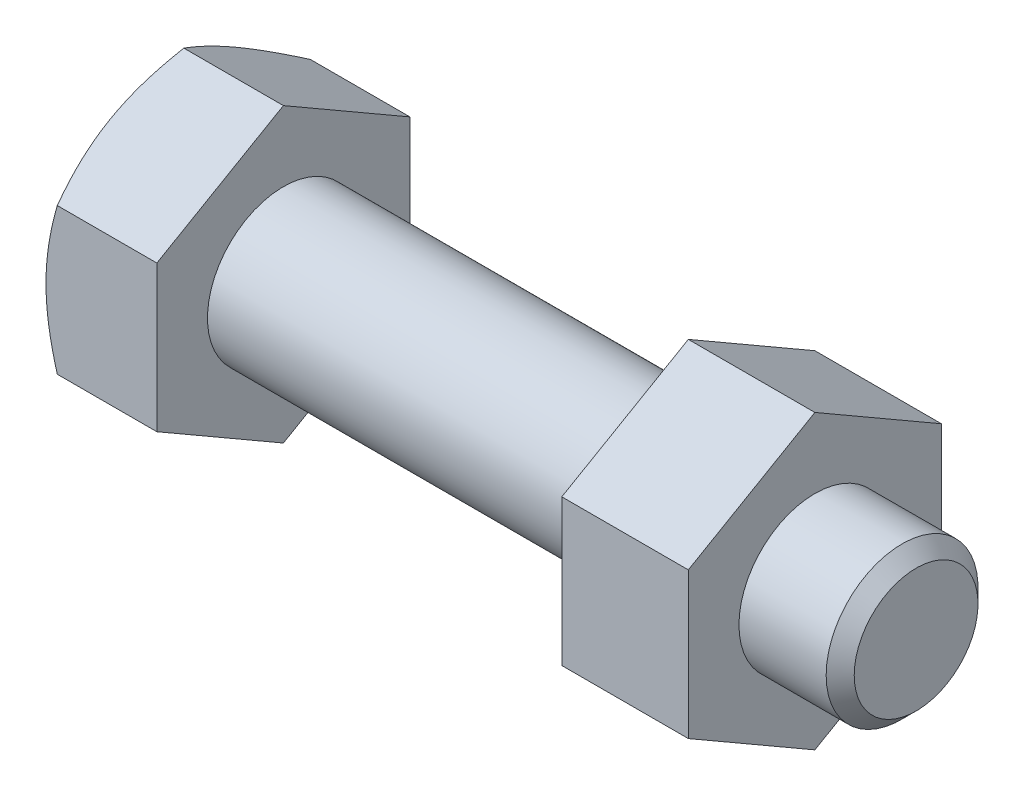
SolidWorks part; units mm, degrees
extrude "BaseHead" add sketch "Sketch1" along normal blind 4.38
sketch "Sketch1" plane through (0, 0, 0) normal (1, 0, 0) x (0, 0, -1)
  line L0 (5, 2.8868) -> (5, -2.8868)
  line L1 (-5, 2.8868) -> (-5, -2.8868)
  line L2 (5, -2.8868) -> (0, -5.7735)
  line L3 (0, -5.7735) -> (-5, -2.8868)
  line L4 (5, 2.8868) -> (0, 5.7735)
  line L5 (0, 5.7735) -> (-5, 2.8868)
  dimension "Width_flats" = 10
  dimension "D2" = 120
  dimension "D3" = 5
  dimension "D4" = 5
  dimension "D5" = 5
material "AISI 304"
ref_plane "Plane1" through (0, 0, 0) normal (0, 0, 1) x (1, 0, 0)
ref_plane "Plane2" through (0, 0, 0) normal (0, 1, 0) x (1, 0, 0)
ref_plane "Plane3" through (0, 0, 0) normal (1, 0, 0) x (0, 0, -1)
sketch "BodySke" plane through (0, 0, 0) normal (0, 0, 1) x (1, 0, 0)
  line L0 (0, 2.8868) -> (0, -2.8868) construction
  line L1 (0, 0) -> (29.38, 0)
  line L2 (0, 0) -> (0, 3)
  line L3 (0, 3) -> (28.8255, 3)
  line L4 (29.38, 0) -> (29.38, 2.4455)
  line L5 (4.38, 5.7735) -> (4.38, 2.8868) construction
  line L6 (29.38, 2.4455) -> (28.8255, 3)
  line L7 (0, 0) -> (96.52, 0) construction
  line L8 (29.38, -2.4455) -> (28.8255, -3) construction
  line L9 (0, -3) -> (28.8255, -3) construction
  line L10 (5.38, 15.24) -> (5.38, -1.27) construction
  line L11 (11.38, 15.24) -> (11.38, -1.27) construction
  line L12 (4.38, 2.8868) -> (4.38, -2.8868) construction
  dimension "Diameter" = 6
  dimension "Advance" = 1
revolve "BaseBody" add sketch "BodySke"
cosmetic thread "ThreadCosmetic" [suppressed]
fillet "HeadFillet" [suppressed] radius 0.25
sketch "Sketch3" plane through (0, 0, 0) normal (0, 0, 1) x (1, 0, 0)
  line L0 (0, 5) -> (3.3333, 10.7735)
  line L1 (0, 5.7735) -> (0, 2.8868) construction
  line L2 (3.3333, 10.7735) -> (3.3333, 15.7735)
  line L3 (3.3333, 15.7735) -> (-10, 15.7735)
  line L4 (-10, 15.7735) -> (-10, 5)
  line L5 (-10, 5) -> (0, 5)
  line L6 (0, 0) -> (99.06, 0) construction
  line L7 (4.38, 5.7735) -> (0, 5.7735) construction
  dimension "D4" = 5
  dimension "D1" = 5
  dimension "D2" = 5
  dimension "D3" = 10
  dimension "Head_ch_ang" = 30
revolve "HeadChamfer" cut sketch "Sketch3" angle 360 about L6
sketch "ThdSchSke" plane through (0, 0, 0) normal (0, 0, 1) x (1, 0, 0)
  line L0 (11.38, -2.4455) -> (10.9917, -3)
  line L1 (11.38, -2.4455) -> (11.7683, -3)
  line L2 (11.7683, -3) -> (11.7683, -3.75)
  line L3 (-3.175, 0) -> (5.1513, 0) construction
  line L5 (11.7683, -3.75) -> (10.9917, -3.75)
  line L6 (10.9917, -3.75) -> (10.9917, -3)
  dimension "Thread_minor" = 4.891
  dimension "Diameter" = 6
  dimension "Start" = 11.38
revolve "ThreadSchematic" [suppressed] cut sketch "ThdSchSke" angle 360 about L3
pattern_linear "ThdSchPat" [suppressed]
ref_plane "Plane4" through (25.38, 0, 0) normal (1, 0, 0) x (0, 0, -1)
sketch "Sketch4" plane through (25.38, 0, 0) normal (1, 0, 0) x (0, 0, -1)
  line L1 (0, 5.7735) -> (-5, 2.8868)
  line L2 (-5, 2.8868) -> (-5, -2.8868)
  line L3 (-5, -2.8868) -> (0, -5.7735)
  line L4 (0, -5.7735) -> (5, -2.8868)
  line L5 (5, -2.8868) -> (5, 2.8868)
  line L6 (5, 2.8868) -> (0, 5.7735)
  circle A0 centre (0, 0) radius 5 construction
  dimension "D1" = 10
extrude "Boss-Extrude1" add sketch "Sketch4" against normal blind 5
equation "\"D3@Sketch1\" = \"Width_flats@Sketch1\" / 2"
equation "\"D4@Sketch1\" = \"D3@Sketch1\""
equation "\"D5@Sketch1\" = \"D4@Sketch1\""
equation "\"Thread_minor@ThreadCosmetic\" = \"Minor_dia@BodySke\""
equation "\"D1@Sketch3\" = \"Width_flats@Sketch1\" / 2"
equation "' \"D1@Sketch4\" = \"Width_flats@Sketch1\""
equation "\"Thread_length@ThreadCosmetic\" = ((sgn( (\"Length@BodySke\" - \"Advance@BodySke\" ) - \"Thread_nom@BodySke\" )-1)*( (\"Length@BodySke\" - \"Advance@BodySke\" ) - \"Thread_nom@BodySke\" ))/-2+ \"Thread_nom@BodySke\""
equation "\"Thread_minor@ThdSchSke\" = \"Minor_dia@BodySke\""
equation "\"Diameter@ThdSchSke\" = \"Diameter@BodySke\""
equation "\"Overcut@ThdSchSke\" = \"Diameter@BodySke\" * 1.25"
equation "\"Start@ThdSchSke\" = \"Head_ht@BaseHead\" + \"Length@BodySke\" - \"Thread_length@ThreadCosmetic\"  '---Non-countersunk---"
equation "\"Num_threads@ThdSchPat\" = int( \"Thread_length@ThreadCosmetic\" / \"Advance@BodySke\" + 0.999 )  + 1"
equation "\"Advance@ThdSchPat\" = \"Thread_length@ThreadCosmetic\" /  (\"Num_threads@ThdSchPat\" - 1) 'relax it"
equation "\"Num_threads@ThdSchPat\" = \"Num_threads@ThdSchPat\" - sgn( \"Num_threads@ThdSchPat\" - 1) '---chamfered tips only---"
